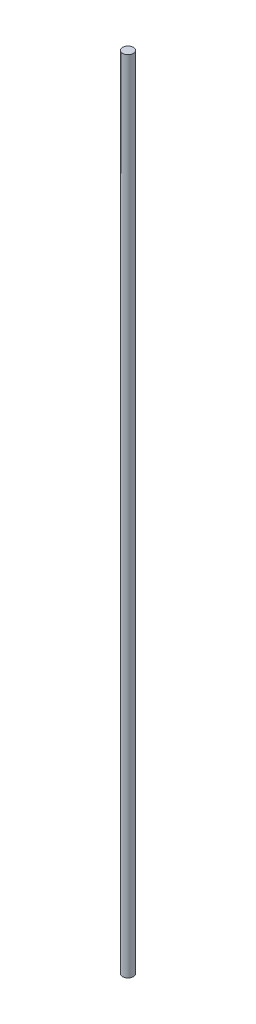
SolidWorks part; units mm, degrees
ref_plane "Front Plane" through (0, 0, 0) normal (0, 0, 1) x (1, 0, 0)
ref_plane "Top Plane" through (0, 0, 0) normal (0, 1, 0) x (1, 0, 0)
ref_plane "Right Plane" through (0, 0, 0) normal (1, 0, 0) x (0, 0, -1)
sketch "Sketch1" plane through (0, 0, 0) normal (0, 1, 0) x (1, 0, 0)
  circle A0 centre (0, 0) radius 2
  dimension "D1" = 4
extrude "Boss-Extrude1" add sketch "Sketch1" along normal blind 300
